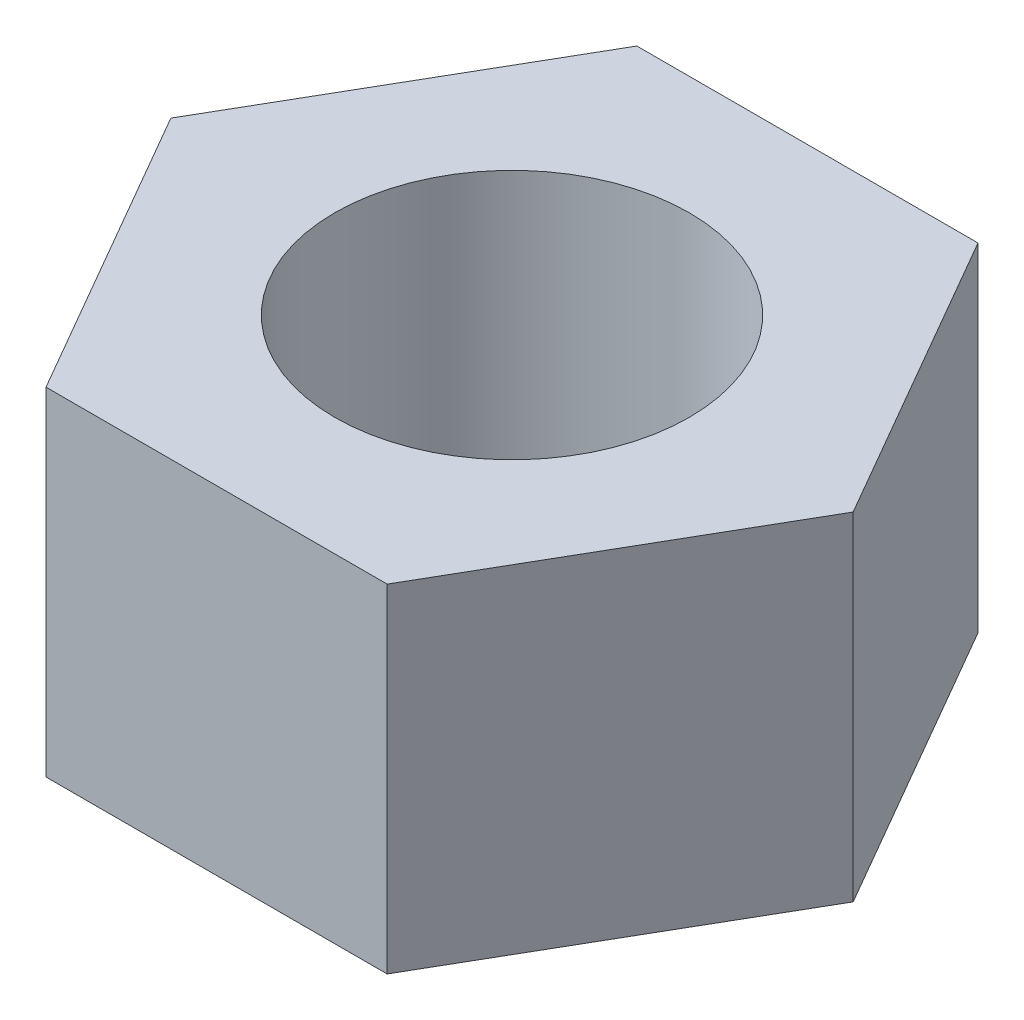
SolidWorks part; units mm, degrees
ref_plane "Front Plane" through (0, 0, 0) normal (0, 0, 1) x (1, 0, 0)
ref_plane "Top Plane" through (0, 0, 0) normal (0, 1, 0) x (1, 0, 0)
ref_plane "Right Plane" through (0, 0, 0) normal (1, 0, 0) x (0, 0, -1)
sketch "Sketch1" plane through (0, 0, 0) normal (0, 1, 0) x (1, 0, 0)
  line L1 (4.0415, 0) -> (2.0207, 3.5)
  line L2 (2.0207, 3.5) -> (-2.0207, 3.5)
  line L3 (-2.0207, 3.5) -> (-4.0415, 0)
  line L4 (-4.0415, 0) -> (-2.0207, -3.5)
  line L5 (-2.0207, -3.5) -> (2.0207, -3.5)
  line L6 (2.0207, -3.5) -> (4.0415, 0)
  circle A0 centre (0, 0) radius 3.5 construction
  circle A1 centre (0, 0) radius 2.1
  dimension "D2" = 4.2
  dimension "D1" = 7
extrude "Boss-Extrude1" add sketch "Sketch1" along normal blind 4
